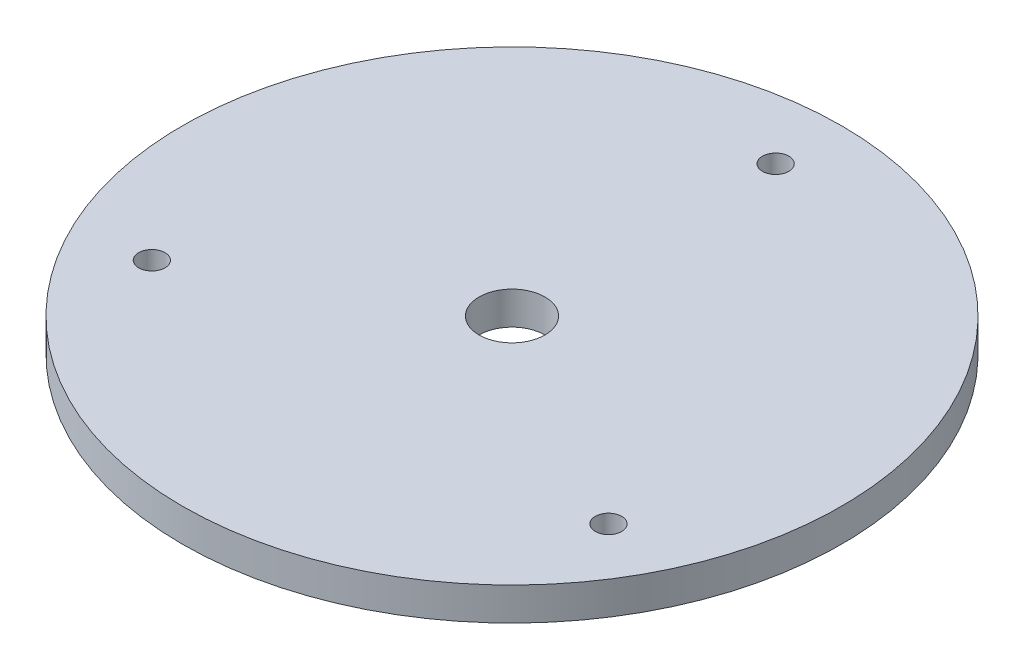
SolidWorks part; units mm, degrees
ref_plane "Alzado" through (0, 0, 0) normal (0, 0, 1) x (1, 0, 0)
ref_plane "Planta" through (0, 0, 0) normal (0, 1, 0) x (1, 0, 0)
ref_plane "Vista lateral" through (0, 0, 0) normal (1, 0, 0) x (0, 0, -1)
sketch "Croquis1" plane through (0, 0, 0) normal (0, 1, 0) x (1, 0, 0)
  line L0 (-86.6025, -50) -> (0, 0) construction
  line L1 (0, 0) -> (86.6025, -50) construction
  line L5 (0, 0) -> (0, 100) construction
  circle A0 centre (0, 0) radius 100
  circle A1 centre (0, 0) radius 10
  circle A2 centre (-69.282, -40) radius 4
  circle A3 centre (69.282, -40) radius 4
  circle A4 centre (0, 80) radius 4
  dimension "D1" = 120
  dimension "D2" = 120
  dimension "D3" = 80
  dimension "D4" = 80
  dimension "D5" = 80
extrude "Saliente-Extruir1" add sketch "Croquis1" along normal blind 10
